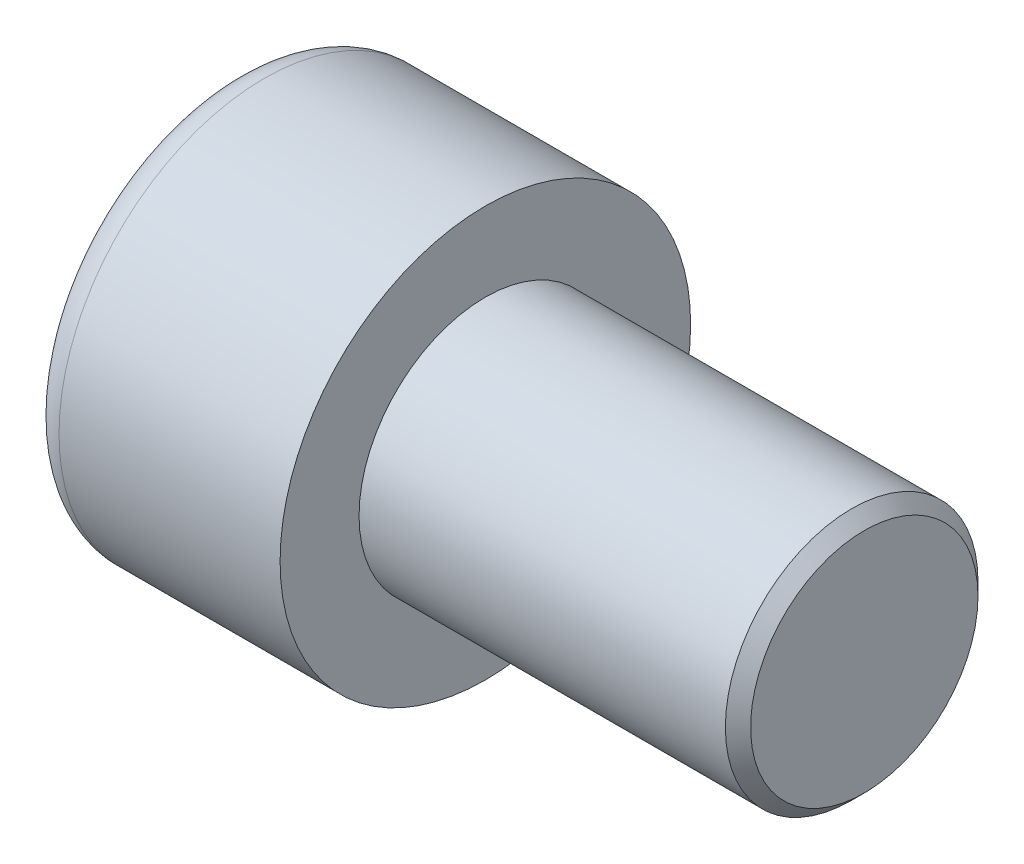
SolidWorks part; units mm, degrees
ref_plane "Front" through (0, 0, 0) normal (0, 0, 1) x (1, 0, 0)
ref_plane "Top" through (0, 0, 0) normal (0, 1, 0) x (1, 0, 0)
ref_plane "Right" through (0, 0, 0) normal (1, 0, 0) x (0, 0, -1)
other "Configuration Table"
sketch "Sketch1" plane through (0, 0, 0) normal (1, 0, 0) x (0, 0, -1)
  circle A0 centre (0, 0) radius 6.5
  dimension "dk" = 13
extrude "BaseHead" add sketch "Sketch1" along normal blind 8
sketch "Sketch2" plane through (8, 0, 0) normal (1, 0, 0) x (0, 0, -1)
  circle A0 centre (0, 0) radius 4
  dimension "d" = 8
extrude "BaseBody" add sketch "Sketch2" along normal blind 12
cosmetic thread "ThreadCosmetic1" [suppressed] parameters "b"=12, "D2"=6.647
sketch "Sketch3" plane through (0, 0, 0) normal (1, 0, 0) x (0, 0, -1)
  line L1 (3.4641, 0) -> (1.7321, 3)
  line L2 (1.7321, 3) -> (-1.7321, 3)
  line L3 (-1.7321, 3) -> (-3.4641, 0)
  line L4 (-3.4641, 0) -> (-1.7321, -3)
  line L5 (-1.7321, -3) -> (1.7321, -3)
  line L6 (1.7321, -3) -> (3.4641, 0)
  circle A0 centre (0, 0) radius 3 construction
  dimension "s" = 6
  dimension "e" = 6.9282
extrude "HexagonSocket" cut sketch "Sketch3" along normal blind 4
sketch "Sketch4" plane through (-4.1961, 0.75, 0) normal (0, 0, 1) x (-1, 0, 0)
  line L0 (-8.1961, 3.75) -> (-9.9282, 0.75)
  line L2 (-9.9282, 0.75) -> (-8.1961, 0.75)
  line L3 (-8.1961, 0.75) -> (-8.1961, 3.75)
  line L4 (-5.0351, 0.75) -> (0.839, 0.75) construction
  line L5 (-24.1961, 0.75) -> (-12.1961, 0.75) construction
  line L6 (-12.1961, 0.75) -> (-4.1961, 0.75) construction
  dimension "m" = 60
revolve "Cut-Revolve1" cut sketch "Sketch4" angle 360 about L4
fillet "HeadFillet" [suppressed] radius 0.4
fillet "TopFillet" radius 1 1 edges at (0, 0, -6.5)
chamfer "Chamfer1" distance 0.4 angle 45 1 edges at (20, 0, -4)
sketch "Sketch5" plane through (0, 0, 0) normal (0, 0, 1) x (1, 0, 0)
  line L0 (19.6, 3.4141) -> (19.9382, 4)
  line L1 (19.9382, 4) -> (19.9382, 4.6765)
  line L2 (19.9382, 4.6765) -> (19.2618, 4.6765)
  line L3 (19.2618, 4.6765) -> (19.2618, 4)
  line L4 (19.2618, 4) -> (19.6, 3.4141)
  line L5 (0, 0) -> (7.8886, 0) construction
  line L6 (19.6, -4) -> (19.6, 4) construction
  dimension "D1" = 8
  dimension "D2" = 0.6765
revolve "Cut-Revolve10" [suppressed] cut sketch "Sketch5" angle 360 about L5
pattern_linear "LPattern10" [suppressed] count 15 spacing 0.8118 along (1, 0, 0)
equation "\"r1@TopFillet\" = \"d@Sketch2\" / 8"
equation "\"D1@Chamfer1\" = \"r@HeadFillet\""
equation "\"D1@Sketch5\" = \"d@Sketch2\""
equation "\"D2@Sketch5\" =  ( \"d@Sketch2\" - \"D2@ThreadCosmetic1\" )  / 2"
equation "\"D3@LPattern10\" = \"D2@Sketch5\" * 1.2"
equation "\"D1@LPattern10\" = \"b@ThreadCosmetic1\" / \"D3@LPattern10\""
